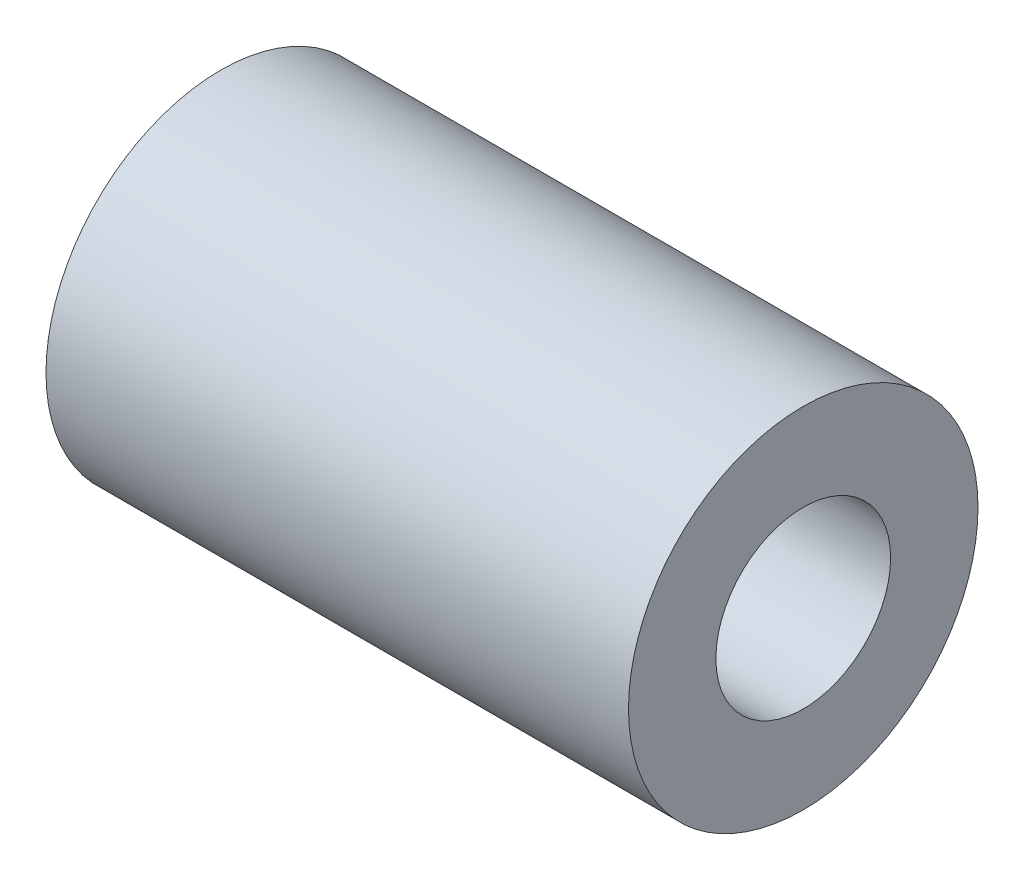
SolidWorks part; units mm, degrees
material "普通碳钢"
ref_plane "前视" through (0, 0, 0) normal (0, 0, 1) x (1, 0, 0)
ref_plane "上视" through (0, 0, 0) normal (0, 1, 0) x (1, 0, 0)
ref_plane "右视" through (0, 0, 0) normal (1, 0, 0) x (0, 0, -1)
sketch "草图1" plane through (0, 0, 0) normal (1, 0, 0) x (0, 0, -1)
  circle A0 centre (0, 0) radius 3
  circle A1 centre (0, 0) radius 1.5
  dimension "D1" = 6
  dimension "D2" = 3
extrude "凸台-拉伸1" add sketch "草图1" along normal blind 10
